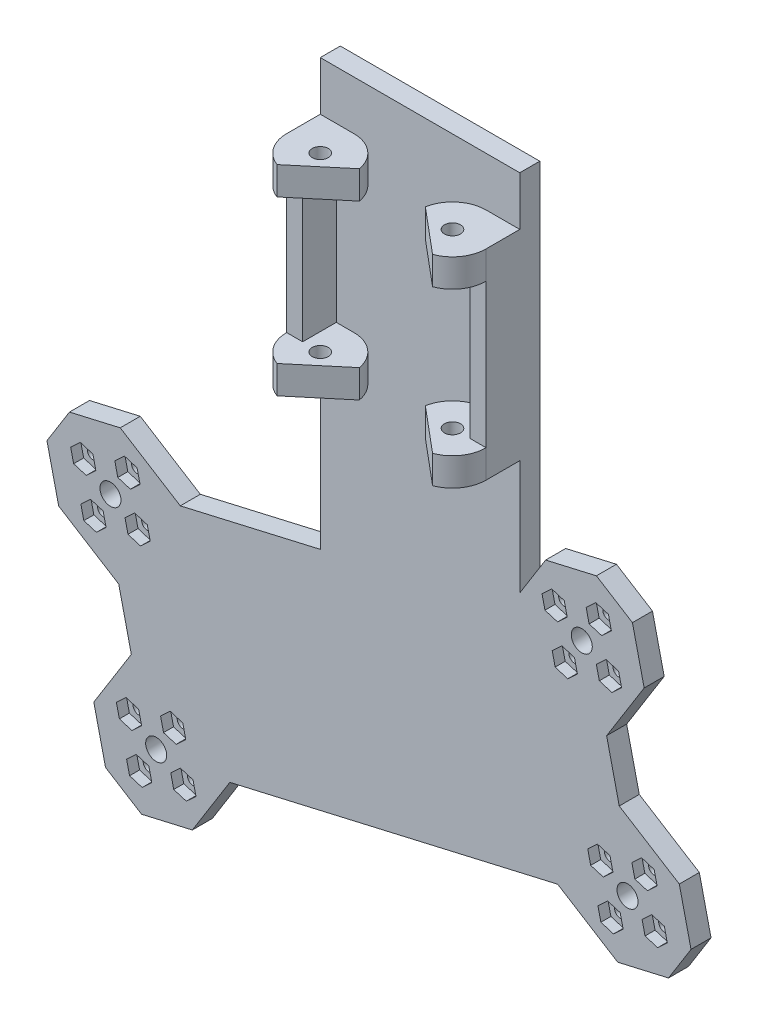
SolidWorks part; units mm, degrees
ref_plane "Front Plane" through (0, 0, 0) normal (0, 0, 1) x (1, 0, 0)
ref_plane "Top Plane" through (0, 0, 0) normal (0, 1, 0) x (1, 0, 0)
ref_plane "Right Plane" through (0, 0, 0) normal (1, 0, 0) x (0, 0, -1)
sketch "Sketch1" plane through (0, 0, 0) normal (0, 1, 0) x (1, 0, 0)
  line L0 (0, 22.8391) -> (0, -19.8342) construction
  line L1 (-35.1495, 0) -> (37.3645, 0) construction
  line L2 (-24.9, 0) -> (-24.9, 13.4)
  line L3 (-24.9, 13.4) -> (24.9, 13.4)
  line L4 (24.9, 0) -> (24.9, 13.4)
  line L5 (-19.4124, -7.879) -> (-8.235, 1.5)
  line L6 (19.4124, -7.879) -> (8.235, 1.5)
  line L7 (16.5, 8.4) -> (-16.5, 8.4)
  arc A0 (19.4124, -7.879) -> (24.9, 0) centre (16.5, 0) ccw
  arc A1 (-19.4124, -7.879) -> (-24.9, 0) centre (-16.5, 0) cw
  arc A2 (-16.5, 8.4) -> (-8.235, 1.5) centre (-16.5, 0) cw
  arc A3 (16.5, 8.4) -> (8.235, 1.5) centre (16.5, 0) ccw
  circle A4 centre (-16.5, 0) radius 8.4 construction
  circle A5 centre (16.5, 0) radius 8.4 construction
  point P14 (0, 13.4)
  dimension "D1" = 16.8
  dimension "D2" = 33
  dimension "D3" = 5
  dimension "D4" = 130
  dimension "D5" = 1.5
  dimension "D6" = 13.4
extrude "Boss-Extrude2" add sketch "Sketch1" along normal blind 7
sketch "Sketch3" plane through (0, 7, 0) normal (0, 1, 0) x (1, 0, 0)
  circle A0 centre (-16.5, 0) radius 2
  circle A1 centre (16.5, 0) radius 2
  dimension "D1" = 4
extrude "Cut-Extrude2" cut sketch "Sketch3" against normal through all both and the other way through all
sketch "Sketch4" plane through (0, 7, 0) normal (0, 1, 0) x (1, 0, 0)
  line L0 (-24.9, 13.4) -> (-24.9, 0)
  line L1 (-24.9, 13.4) -> (24.9, 13.4)
  line L2 (24.9, 13.4) -> (24.9, 0)
  line L3 (0, 13.4) -> (0, 0) construction
  line L4 (-16.5, 8.4) -> (16.5, 8.4)
  line L5 (-16.5, 8.4) -> (16.5, 8.4) construction
  line L6 (16.5, 8.4) -> (20.9, 8.4)
  line L7 (20.9, 8.4) -> (20.9, 0)
  line L8 (20.9, 0) -> (24.9, 0)
  line L9 (-20.9, 0) -> (-24.9, 0)
  line L10 (-20.9, 8.4) -> (-20.9, 0)
  line L11 (-16.5, 8.4) -> (-20.9, 8.4)
  circle A0 centre (-16.5, 0) radius 3.7 construction
  point P21 (0, 8.4)
  dimension "D2" = 7.4
  dimension "D1" = 4
extrude "Boss-Extrude3" add sketch "Sketch4" along normal blind 36
sketch "Sketch5" plane through (0, 43, 0) normal (0, 1, 0) x (1, 0, 0)
  line L12 (-24.9, 13.4) -> (-24.9, 0)
  line L13 (24.9, 13.4) -> (-24.9, 13.4)
  line L14 (24.9, 0) -> (24.9, 13.4)
  line L15 (8.235, 1.5) -> (19.4124, -7.879)
  line L16 (-16.5, 8.4) -> (16.5, 8.4)
  line L17 (-19.4124, -7.879) -> (-8.235, 1.5)
  line L18 (-24.9, 13.4) -> (-24.9, 0)
  line L19 (24.9, 13.4) -> (-24.9, 13.4)
  line L20 (24.9, 0) -> (24.9, 13.4)
  line L21 (8.235, 1.5) -> (19.4124, -7.879)
  line L22 (-16.5, 8.4) -> (16.5, 8.4)
  line L23 (-19.4124, -7.879) -> (-8.235, 1.5)
  circle A0 centre (-16.5, 0) radius 2 construction
  circle A1 centre (16.5, 0) radius 2
  circle A2 centre (16.5, 0) radius 2 construction
  circle A4 centre (-16.5, 0) radius 2
  arc A8 (-24.9, 0) -> (-19.4124, -7.879) centre (-16.5, 0) ccw
  arc A9 (19.4124, -7.879) -> (24.9, 0) centre (16.5, 0) ccw
  arc A10 (16.5, 8.4) -> (8.235, 1.5) centre (16.5, 0) ccw
  arc A11 (-8.235, 1.5) -> (-16.5, 8.4) centre (-16.5, 0) ccw
  arc A12 (-24.9, 0) -> (-19.4124, -7.879) centre (-16.5, 0) ccw
  arc A13 (19.4124, -7.879) -> (24.9, 0) centre (16.5, 0) ccw
  arc A14 (16.5, 8.4) -> (8.235, 1.5) centre (16.5, 0) ccw
  arc A15 (-8.235, 1.5) -> (-16.5, 8.4) centre (-16.5, 0) ccw
  dimension "D1" = 0
extrude "Boss-Extrude4" add sketch "Sketch5" along normal blind 7
sketch "Sketch13" plane through (0, 50, 0) normal (0, 1, 0) x (1, 0, 0)
  line L0 (24.9, 0) -> (24.9, 13.4) construction
  line L5 (-24.9, 13.4) -> (24.9, 13.4)
  line L6 (-24.9, 13.4) -> (-24.9, 8.4)
  line L7 (-24.9, 8.4) -> (24.9, 8.4)
  line L8 (24.9, 13.4) -> (24.9, 8.4)
  line L9 (-16.5, 8.4) -> (16.5, 8.4) construction
extrude "Boss-Extrude6" add sketch "Sketch13" along normal blind 12.25
sketch "Sketch15" plane through (0, 0, 0) normal (0, -1, 0) x (1, 0, 0)
  line L0 (24.9, 0) -> (24.9, -13.4) construction
  line L1 (-24.9, -13.4) -> (24.9, -13.4)
  line L2 (-24.9, -13.4) -> (-24.9, -8.4)
  line L3 (-24.9, -8.4) -> (24.9, -8.4)
  line L4 (24.9, -13.4) -> (24.9, -8.4)
  line L5 (-16.5, -8.4) -> (16.5, -8.4) construction
extrude "Boss-Extrude7" add sketch "Sketch15" along normal blind 30
sketch "Sketch12" plane through (0, 0, -13.4) normal (0, 0, -1) x (-1, 0, 0)
  line L8 (-24.9, -30) -> (19.5541, -30) construction
  line L9 (24.9, -30) -> (24.9, -31.2342) construction
  line L10 (24.9, -41.4972) -> (-24.9, -30) construction
  line L19 (0, -35.7486) -> (-6.7485, -64.9797) construction
  line L20 (2.2495, -26.0049) -> (-51.3408, -13.6326)
  line L21 (-24.9, -30) -> (-25.6851, -33.4006) construction
  line L22 (0, -35.7486) -> (5.7273, -10.9407) construction
  line L23 (2.2495, -26.0049) -> (19.5541, -30)
  line L24 (-51.3408, -13.6326) -> (-69.3369, -91.5822)
  line L25 (-69.3369, -91.5822) -> (-15.7466, -103.9545)
  line L26 (94.8147, -47.3753) -> (76.8186, -125.3249)
  line L27 (76.8186, -125.3249) -> (-15.7466, -103.9545)
  line L28 (-6.7485, -64.9797) -> (-39.5375, -57.4098) construction
  line L29 (24.9, -30) -> (24.9, -31.2342)
  line L30 (24.9, -30) -> (19.5541, -30)
  line L31 (24.9, -31.2342) -> (94.8147, -47.3753)
  line L32 (24.9, -31.2342) -> (24.9, -41.4972) construction
  line L33 (19.5541, -30) -> (24.9, -30) construction
  point P14 (19.2721, -30)
  point P16 (5.7273, -10.9407)
  point P18 (0, 0)
  point P21 (-25.6851, -33.4006)
  dimension "D1" = 13
  dimension "D2" = 30
  dimension "D3" = 80
  dimension "D4" = 55
  dimension "D5" = 95
extrude "Boss-Extrude8" add sketch "Sketch12" against normal blind 5
sketch "Sketch16" plane through (0, 0, -8.4) normal (0, 0, 1) x (1, 0, 0)
  line L0 (60.3389, -52.6074) -> (-85.8166, -86.3501) construction
  line L1 (51.3408, -13.6326) -> (69.3369, -91.5822) construction
  line L2 (-76.8186, -125.3249) -> (-94.8147, -47.3753) construction
  line L3 (-3.7408, -108.4535) -> (-21.7369, -30.5039) construction
  line L4 (69.3369, -91.5822) -> (-76.8186, -125.3249) construction
  line L5 (24.9, -19.737) -> (51.3408, -13.6326) construction
  line L6 (-24.9, -31.2342) -> (24.9, -19.737) construction
  line L7 (40.3806, -31.1727) -> (54.6308, -27.8828) construction
  line L8 (40.3806, -31.1727) -> (47.165, -35.412) construction
  line L16 (45.3602, -27.5948) -> (47.767, -25.3505) construction
  line L17 (47.767, -25.3505) -> (47.0268, -22.1439) construction
  line L18 (47.0268, -22.1439) -> (43.8797, -21.1817) construction
  line L19 (43.8797, -21.1817) -> (41.4728, -23.4261) construction
  line L20 (41.4728, -23.4261) -> (42.2131, -26.6327) construction
  line L21 (42.2131, -26.6327) -> (45.3602, -27.5948) construction
  circle A0 centre (40.3806, -31.1727) radius 2.625
  circle A4 centre (40.3806, -31.1727) radius 8 construction
  circle A22 centre (47.165, -35.412) radius 1.5
  circle A23 centre (36.1412, -37.9571) radius 1.5
  circle A24 centre (33.5962, -26.9333) radius 1.5
  circle A25 centre (44.6199, -24.3883) radius 1.5
  circle A26 centre (44.6199, -24.3883) radius 2.85 construction
  circle A27 centre (47.5575, -87.4063) radius 1.5
  circle A28 centre (45.0125, -76.3826) radius 1.5
  circle A29 centre (58.5812, -84.8613) radius 1.5
  circle A30 centre (56.0362, -73.8376) radius 1.5
  circle A31 centre (51.7969, -80.622) radius 2.625
  circle A32 centre (-73.0352, -51.5511) radius 1.5
  circle A33 centre (-84.059, -54.0962) radius 1.5
  circle A34 centre (-81.5139, -65.1199) radius 1.5
  circle A35 centre (-77.2746, -58.3355) radius 2.625
  circle A36 centre (-70.4902, -62.5749) radius 1.5
  circle A37 centre (-61.619, -101.0004) radius 1.5
  circle A38 centre (-72.6427, -103.5454) radius 1.5
  circle A39 centre (-70.0977, -114.5692) radius 1.5
  circle A40 centre (-65.8583, -107.7848) radius 2.625
  circle A41 centre (-59.0739, -112.0242) radius 1.5
  point P16 (0, 0)
  point P31 (40.3806, -31.1727)
  point P36 (40.3806, -31.1727)
  dimension "D1" = 5.25
  dimension "D4" = 16
  dimension "D5" = 45
  dimension "D6" = 3
  dimension "D2" = 14.625
  dimension "D3" = 14.625
  dimension "D10" = 5.7
  dimension "D7" = 4
extrude "Cut-Extrude3" cut sketch "Sketch16" against normal through all both and the other way through all
sketch "Sketch22" plane through (0, 0, -8.4) normal (0, 0, 1) x (1, 0, 0)
  line L0 (51.3408, -13.6326) -> (69.3369, -91.5822) construction
  line L1 (32.8559, -23.7268) -> (30.4491, -25.9712)
  line L2 (30.4491, -25.9712) -> (31.1894, -29.1777)
  line L3 (31.1894, -29.1777) -> (34.3365, -30.1399)
  line L4 (34.3365, -30.1399) -> (36.7433, -27.8955)
  line L5 (36.7433, -27.8955) -> (36.003, -24.6889)
  line L6 (36.003, -24.6889) -> (32.8559, -23.7268)
  line L7 (43.8797, -21.1817) -> (41.4728, -23.4261)
  line L8 (41.4728, -23.4261) -> (42.2131, -26.6327)
  line L9 (42.2131, -26.6327) -> (45.3602, -27.5948)
  line L10 (45.3602, -27.5948) -> (47.767, -25.3505)
  line L11 (47.767, -25.3505) -> (47.0268, -22.1439)
  line L12 (47.0268, -22.1439) -> (43.8797, -21.1817)
  line L13 (46.4247, -32.2055) -> (44.0179, -34.4499)
  line L14 (44.0179, -34.4499) -> (44.7582, -37.6564)
  line L15 (44.7582, -37.6564) -> (47.9053, -38.6186)
  line L16 (47.9053, -38.6186) -> (50.3121, -36.3742)
  line L17 (50.3121, -36.3742) -> (49.5718, -33.1676)
  line L18 (49.5718, -33.1676) -> (46.4247, -32.2055)
  line L19 (38.548, -35.7127) -> (35.4009, -34.7505)
  line L20 (35.4009, -34.7505) -> (32.9941, -36.9949)
  line L21 (32.9941, -36.9949) -> (33.7344, -40.2015)
  line L22 (33.7344, -40.2015) -> (36.8815, -41.1636)
  line L23 (36.8815, -41.1636) -> (39.2883, -38.9192)
  line L24 (39.2883, -38.9192) -> (38.548, -35.7127)
  line L25 (60.3389, -52.6074) -> (-85.8166, -86.3501) construction
  line L26 (-76.8186, -125.3249) -> (-94.8147, -47.3753) construction
  line L27 (-24.9, -31.2342) -> (24.9, -19.737) construction
  line L28 (-12.7389, -69.4787) -> (-3.7408, -108.4535) construction
  line L30 (47.4193, -74.1382) -> (48.1596, -77.3448)
  line L31 (44.2722, -73.1761) -> (47.4193, -74.1382)
  line L32 (41.8654, -75.4204) -> (44.2722, -73.1761)
  line L33 (42.6057, -78.627) -> (41.8654, -75.4204)
  line L34 (45.7528, -79.5892) -> (42.6057, -78.627)
  line L35 (48.1596, -77.3448) -> (45.7528, -79.5892)
  line L36 (50.7046, -88.3685) -> (48.2978, -90.6129)
  line L37 (49.9643, -85.162) -> (50.7046, -88.3685)
  line L38 (46.8172, -84.1998) -> (49.9643, -85.162)
  line L39 (44.4104, -86.4442) -> (46.8172, -84.1998)
  line L40 (45.1507, -89.6507) -> (44.4104, -86.4442)
  line L41 (48.2978, -90.6129) -> (45.1507, -89.6507)
  line L42 (61.7283, -85.8235) -> (59.3215, -88.0679)
  line L43 (60.9881, -82.6169) -> (61.7283, -85.8235)
  line L44 (57.841, -81.6548) -> (60.9881, -82.6169)
  line L45 (55.4341, -83.8992) -> (57.841, -81.6548)
  line L46 (56.1744, -87.1057) -> (55.4341, -83.8992)
  line L47 (59.3215, -88.0679) -> (56.1744, -87.1057)
  line L48 (59.1833, -74.7997) -> (56.7765, -77.0441)
  line L49 (58.443, -71.5932) -> (59.1833, -74.7997)
  line L50 (55.2959, -70.631) -> (58.443, -71.5932)
  line L51 (52.8891, -72.8754) -> (55.2959, -70.631)
  line L52 (53.6294, -76.082) -> (52.8891, -72.8754)
  line L53 (56.7765, -77.0441) -> (53.6294, -76.082)
  line L54 (69.3369, -91.5822) -> (-76.8186, -125.3249) construction
  line L55 (-73.2448, -113.607) -> (-72.5045, -116.8136)
  line L56 (-70.838, -111.3626) -> (-73.2448, -113.607)
  line L57 (-67.6909, -112.3248) -> (-70.838, -111.3626)
  line L58 (-66.9506, -115.5314) -> (-67.6909, -112.3248)
  line L59 (-69.3574, -117.7757) -> (-66.9506, -115.5314)
  line L60 (-72.5045, -116.8136) -> (-69.3574, -117.7757)
  line L61 (-62.221, -111.062) -> (-61.4808, -114.2685)
  line L62 (-59.8142, -108.8176) -> (-62.221, -111.062)
  line L63 (-56.6671, -109.7798) -> (-59.8142, -108.8176)
  line L64 (-55.9268, -112.9863) -> (-56.6671, -109.7798)
  line L65 (-58.3337, -115.2307) -> (-55.9268, -112.9863)
  line L66 (-61.4808, -114.2685) -> (-58.3337, -115.2307)
  line L67 (-75.7898, -102.5833) -> (-75.0495, -105.7898)
  line L68 (-73.383, -100.3389) -> (-75.7898, -102.5833)
  line L69 (-70.2359, -101.3011) -> (-73.383, -100.3389)
  line L70 (-69.4956, -104.5076) -> (-70.2359, -101.3011)
  line L71 (-71.9024, -106.752) -> (-69.4956, -104.5076)
  line L72 (-75.0495, -105.7898) -> (-71.9024, -106.752)
  line L73 (-62.3593, -97.7939) -> (-64.7661, -100.0383)
  line L74 (-59.2122, -98.756) -> (-62.3593, -97.7939)
  line L75 (-58.4719, -101.9626) -> (-59.2122, -98.756)
  line L76 (-60.8787, -104.207) -> (-58.4719, -101.9626)
  line L77 (-64.0258, -103.2448) -> (-60.8787, -104.207)
  line L78 (-64.7661, -100.0383) -> (-64.0258, -103.2448)
  line L79 (-72.897, -64.8193) -> (-73.6373, -61.6127)
  line L80 (-69.7499, -65.7814) -> (-72.897, -64.8193)
  line L81 (-67.3431, -63.537) -> (-69.7499, -65.7814)
  line L82 (-68.0834, -60.3305) -> (-67.3431, -63.537)
  line L83 (-71.2305, -59.3683) -> (-68.0834, -60.3305)
  line L84 (-73.6373, -61.6127) -> (-71.2305, -59.3683)
  line L85 (-76.1823, -50.589) -> (-73.7755, -48.3446)
  line L86 (-75.4421, -53.7955) -> (-76.1823, -50.589)
  line L87 (-72.295, -54.7577) -> (-75.4421, -53.7955)
  line L88 (-69.8881, -52.5133) -> (-72.295, -54.7577)
  line L89 (-70.6284, -49.3067) -> (-69.8881, -52.5133)
  line L90 (-73.7755, -48.3446) -> (-70.6284, -49.3067)
  line L91 (-84.661, -64.1577) -> (-82.2542, -61.9134)
  line L92 (-83.9208, -67.3643) -> (-84.661, -64.1577)
  line L93 (-80.7737, -68.3265) -> (-83.9208, -67.3643)
  line L94 (-78.3668, -66.0821) -> (-80.7737, -68.3265)
  line L95 (-79.1071, -62.8755) -> (-78.3668, -66.0821)
  line L96 (-82.2542, -61.9134) -> (-79.1071, -62.8755)
  line L97 (-87.2061, -53.134) -> (-84.7993, -50.8896)
  line L98 (-86.4658, -56.3406) -> (-87.2061, -53.134)
  line L99 (-83.3187, -57.3027) -> (-86.4658, -56.3406)
  line L100 (-80.9119, -55.0583) -> (-83.3187, -57.3027)
  line L101 (-81.6522, -51.8518) -> (-80.9119, -55.0583)
  line L102 (-84.7993, -50.8896) -> (-81.6522, -51.8518)
  circle A0 centre (33.5962, -26.9333) radius 2.85 construction
  circle A1 centre (44.6199, -24.3883) radius 2.85 construction
  circle A2 centre (47.165, -35.412) radius 2.85 construction
  circle A3 centre (36.1412, -37.9571) radius 2.85 construction
  dimension "D1" = 5.7
  dimension "D2" = 5.7
  dimension "D3" = 5.7
  dimension "D4" = 5.7
extrude "Cut-Extrude8" cut sketch "Sketch22" against normal blind 2.5
sketch "Sketch28" plane through (0, 0, -13.4) normal (0, 0, -1) x (-1, 0, 0)
  line L0 (-60.3389, -52.6074) -> (85.8166, -86.3501) construction
  line L1 (-51.3408, -13.6326) -> (-69.3369, -91.5822) construction
  line L2 (76.8186, -125.3249) -> (94.8147, -47.3753) construction
  line L3 (-24.9, -19.737) -> (24.9, -31.2342) construction
  line L4 (3.7408, -108.4535) -> (21.7369, -30.5039) construction
  line L5 (-69.3369, -91.5822) -> (76.8186, -125.3249) construction
  line L6 (-58.0894, -42.8637) -> (88.0661, -76.6064) construction
  line L7 (4.3006, -67.5306) -> (6.8326, -75.8124)
  line L8 (6.8326, -75.8124) -> (15.2709, -77.7606)
  line L9 (15.2709, -77.7606) -> (21.1772, -71.4269)
  line L10 (21.1772, -71.4269) -> (18.6451, -63.145)
  line L11 (18.6451, -63.145) -> (10.2069, -61.1969)
  line L12 (10.2069, -61.1969) -> (4.3006, -67.5306)
  line L27 (-55.8399, -33.12) -> (90.3156, -66.8627) construction
  line L28 (-53.5904, -23.3763) -> (92.5652, -57.119) construction
  line L29 (-51.3408, -13.6326) -> (94.8147, -47.3753) construction
  line L30 (-60.3389, -52.6074) -> (-58.0894, -42.8637) construction
  line L31 (-62.5884, -62.3511) -> (83.5671, -96.0938) construction
  line L32 (-64.8379, -72.0948) -> (81.3176, -105.8375) construction
  line L33 (-67.0874, -81.8385) -> (79.0681, -115.5812) construction
  line L34 (-69.3369, -91.5822) -> (76.8186, -125.3249) construction
  line L35 (-60.3389, -52.6074) -> (-62.5884, -62.3511) construction
  line L36 (20.6179, -112.3499) -> (38.614, -34.4003) construction
  line L37 (37.495, -116.2463) -> (55.491, -38.2967) construction
  line L38 (54.372, -120.1427) -> (72.3681, -42.1931) construction
  line L39 (71.2491, -124.0391) -> (89.2452, -46.0894) construction
  line L40 (3.7408, -108.4535) -> (20.6179, -112.3499) construction
  line L41 (-13.1362, -104.5572) -> (4.8598, -26.6076) construction
  line L42 (-30.0133, -100.6608) -> (-12.0172, -22.7112) construction
  line L43 (-46.8904, -96.7644) -> (-28.8943, -18.8148) construction
  line L44 (-63.7674, -92.868) -> (-45.7713, -14.9184) construction
  line L45 (3.7408, -108.4535) -> (-13.1362, -104.5572) construction
  line L47 (8.7996, -48.0432) -> (11.3316, -56.325)
  line L48 (11.3316, -56.325) -> (19.7699, -58.2732)
  line L49 (19.7699, -58.2732) -> (25.6762, -51.9395)
  line L50 (25.6762, -51.9395) -> (23.1442, -43.6576)
  line L51 (23.1442, -43.6576) -> (14.7059, -41.7095)
  line L52 (14.7059, -41.7095) -> (8.7996, -48.0432)
  line L53 (-10.327, -53.8905) -> (-7.795, -62.1724)
  line L54 (-7.795, -62.1724) -> (0.6433, -64.1205)
  line L55 (0.6433, -64.1205) -> (6.5496, -57.7868)
  line L56 (6.5496, -57.7868) -> (4.0176, -49.505)
  line L57 (4.0176, -49.505) -> (-4.4207, -47.5568)
  line L58 (-4.4207, -47.5568) -> (-10.327, -53.8905)
  line L59 (-5.828, -34.4031) -> (-3.2959, -42.685)
  line L60 (-3.2959, -42.685) -> (5.1424, -44.6331)
  line L61 (5.1424, -44.6331) -> (11.0486, -38.2994)
  line L62 (11.0486, -38.2994) -> (8.5166, -30.0176)
  line L63 (8.5166, -30.0176) -> (0.0783, -28.0694)
  line L64 (0.0783, -28.0694) -> (-5.828, -34.4031)
  line L65 (-14.826, -73.3779) -> (-12.294, -81.6598)
  line L66 (-12.294, -81.6598) -> (-3.8557, -83.6079)
  line L67 (-3.8557, -83.6079) -> (2.0506, -77.2742)
  line L68 (2.0506, -77.2742) -> (-0.4814, -68.9924)
  line L69 (-0.4814, -68.9924) -> (-8.9197, -67.0442)
  line L70 (-8.9197, -67.0442) -> (-14.826, -73.3779)
  line L71 (-29.4536, -59.7379) -> (-26.9215, -68.0197)
  line L72 (-26.9215, -68.0197) -> (-18.4832, -69.9678)
  line L73 (-18.4832, -69.9678) -> (-12.577, -63.6341)
  line L74 (-12.577, -63.6341) -> (-15.109, -55.3523)
  line L75 (-15.109, -55.3523) -> (-23.5473, -53.4041)
  line L76 (-23.5473, -53.4041) -> (-29.4536, -59.7379)
  line L77 (-24.9545, -40.2505) -> (-22.4225, -48.5323)
  line L78 (-22.4225, -48.5323) -> (-13.9842, -50.4804)
  line L79 (-13.9842, -50.4804) -> (-8.0779, -44.1467)
  line L80 (-8.0779, -44.1467) -> (-10.61, -35.8649)
  line L81 (-10.61, -35.8649) -> (-19.0483, -33.9167)
  line L82 (-19.0483, -33.9167) -> (-24.9545, -40.2505)
  circle A0 centre (12.7389, -69.4787) radius 7.5 construction
  circle A1 centre (17.2379, -49.9913) radius 7.5 construction
  circle A2 centre (-1.8887, -55.8387) radius 7.5 construction
  circle A3 centre (2.6103, -36.3513) radius 7.5 construction
  circle A4 centre (-6.3877, -75.3261) radius 7.5 construction
  circle A5 centre (-21.0153, -61.686) radius 7.5 construction
  circle A6 centre (-16.5162, -42.1986) radius 7.5 construction
  point P71 (0, 0)
  dimension "D1" = 15
  dimension "D2" = 5
  dimension "D3" = 10
  dimension "D4" = 5
  dimension "D5" = 10
  dimension "D7" = 17.321
  dimension "D9" = 17.321
  dimension "D6" = 5
  dimension "D8" = 5
extrude "Cut-Extrude9" [suppressed] cut sketch "Sketch28" against normal blind 30
sketch "Sketch30" plane through (0, 0, -13.4) normal (0, 0, -1) x (-1, 0, 0)
  line L0 (24.9, -31.2342) -> (-24.9, -19.737) construction
  line L1 (3.7408, -108.4535) -> (21.7369, -30.5039) construction
  line L2 (-69.3369, -91.5822) -> (76.8186, -125.3249) construction
  line L3 (-60.3389, -52.6074) -> (85.8166, -86.3501) construction
  line L4 (-51.3408, -13.6326) -> (-69.3369, -91.5822) construction
  line L5 (76.8186, -125.3249) -> (94.8147, -47.3753) construction
  line L6 (47.4703, -105.7205) -> (-34.3649, -86.8273)
  line L7 (-34.3649, -86.8273) -> (-49.3564, -96.1951)
  line L8 (-64.7241, -71.6017) -> (-49.7325, -62.234)
  line L9 (-49.7325, -62.234) -> (-48.1593, -55.4193)
  line L10 (-69.3369, -91.5822) -> (-45.0125, -76.3826) construction
  line L11 (47.4703, -105.7205) -> (56.8381, -120.712)
  line L12 (-46.586, -48.6047) -> (-48.1593, -55.4193)
  line L13 (-55.9537, -33.6131) -> (-46.586, -48.6047)
  line L14 (-51.3408, -13.6326) -> (-36.1412, -37.9571) construction
  line L15 (-24.9, -28.5841) -> (-31.3603, -18.2455)
  line L16 (59.8426, -52.1301) -> (74.8341, -42.7624)
  line L17 (81.4315, -105.3443) -> (72.0637, -90.3528)
  line L18 (72.0637, -90.3528) -> (73.637, -83.5382)
  line L19 (90.2018, -67.3558) -> (75.2103, -76.7235)
  line L20 (75.2103, -76.7235) -> (73.637, -83.5382)
  line L21 (59.8426, -52.1301) -> (24.9, -44.063)
  line L22 (-24.9, -19.737) -> (-24.9, -28.5841)
  line L23 (24.9, -31.2342) -> (24.9, -44.063)
  line L24 (-64.7241, -71.6017) -> (-55.9537, -33.6131)
  line L25 (-31.3603, -18.2455) -> (-24.9, -19.737)
  line L26 (-49.3564, -96.1951) -> (56.8381, -120.712)
  line L27 (24.9, -31.2342) -> (74.8341, -42.7624)
  line L28 (90.2018, -67.3558) -> (81.4315, -105.3443)
  point P27 (6.5527, -96.2739)
  dimension "D1" = 29
  dimension "D2" = 12.5
  dimension "D3" = 12.5
extrude "Cut-Extrude11" cut sketch "Sketch30" against normal through all both
chamfer "Chamfer2" distance 7.5 angle 45 4 edges at (-76.8186, -125.3249, -10.9) (-94.8147, -47.3753, -10.9) (51.3408, -13.6326, -10.9) (69.3369, -91.5822, -10.9)
